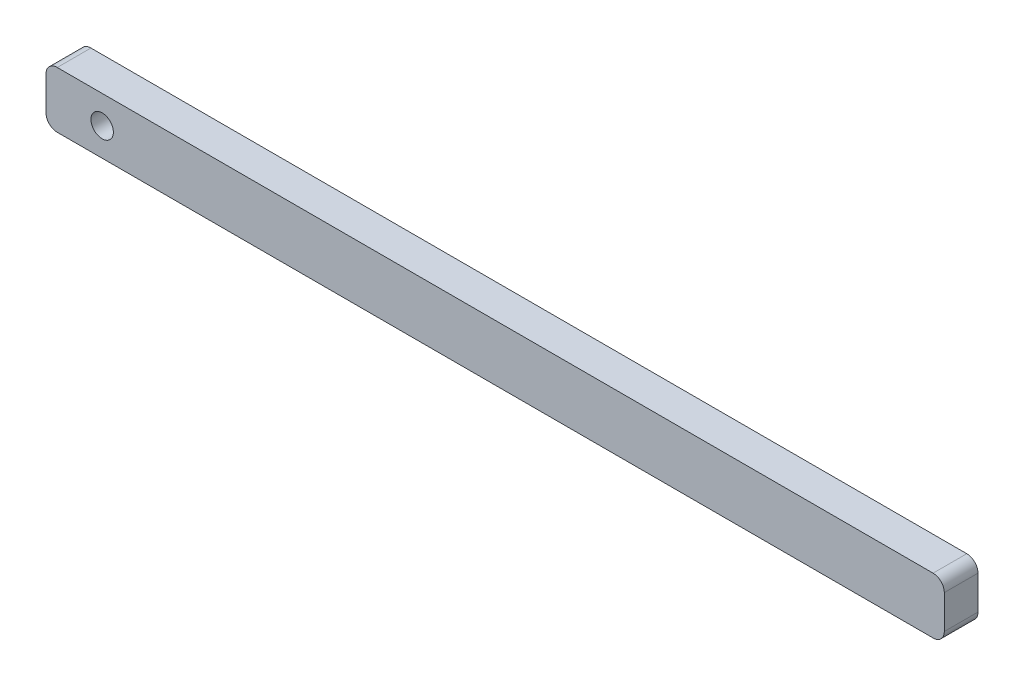
SolidWorks part; units mm, degrees
ref_plane "Front Plane" through (0, 0, 0) normal (0, 0, 1) x (1, 0, 0)
ref_plane "Top Plane" through (0, 0, 0) normal (0, 1, 0) x (1, 0, 0)
ref_plane "Right Plane" through (0, 0, 0) normal (1, 0, 0) x (0, 0, -1)
sketch "Sketch1" plane through (0, 0, 0) normal (0, 0, 1) x (1, 0, 0)
  line L1 (40, 2.5) -> (-40, 2.5)
  line L2 (40, 2.5) -> (40, -2.5)
  line L3 (40, -2.5) -> (-40, -2.5)
  line L4 (-40, 2.5) -> (-40, -2.5)
  line L5 (40, 2.5) -> (-40, -2.5) construction
  line L6 (40, -2.5) -> (-40, 2.5) construction
  point P0 (0, 0)
  dimension "D1" = 80
  dimension "D2" = 5
extrude "Boss-Extrude1" add sketch "Sketch1" along normal blind 3
sketch "Sketch2" plane through (0, 0, 3) normal (0, 0, 1) x (1, 0, 0)
  line L0 (-40, 2.5) -> (-40, -2.5) construction
  line L1 (-40, -2.5) -> (40, -2.5) construction
  circle A0 centre (-35, 0) radius 1
  dimension "D2" = 2
  dimension "D1" = 5
  dimension "D3" = 2.5
extrude "Cut-Extrude1" cut sketch "Sketch2" against normal through all
fillet "Fillet1" radius 1 4 edges at (-40, -2.5, 1.5) (-40, 2.5, 1.5) (40, -2.5, 1.5) (40, 2.5, 1.5)
